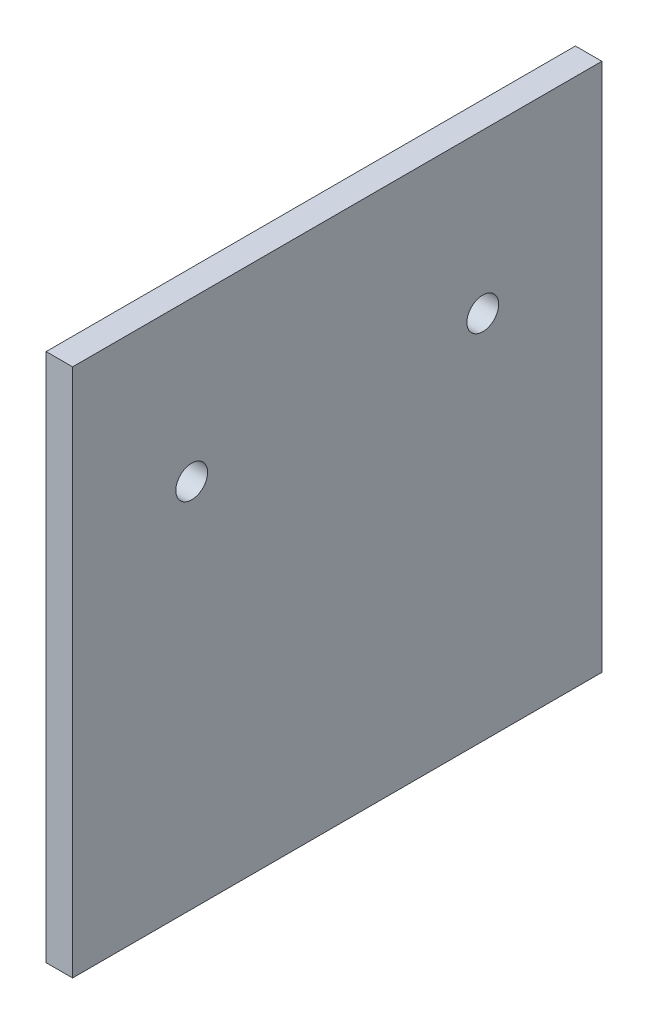
SolidWorks part; units mm, degrees
material "Plain Carbon Steel"
ref_plane "Front Plane" through (0, 0, 0) normal (0, 0, 1) x (1, 0, 0)
ref_plane "Top Plane" through (0, 0, 0) normal (0, 1, 0) x (1, 0, 0)
ref_plane "Right Plane" through (0, 0, 0) normal (1, 0, 0) x (0, 0, -1)
sketch "Sketch1" plane through (0, 0, 0) normal (1, 0, 0) x (0, 0, -1)
  line L1 (-100, -100) -> (100, -100)
  line L2 (-100, -100) -> (-100, 100)
  line L3 (-100, 100) -> (100, 100)
  line L4 (100, -100) -> (100, 100)
  line L5 (-100, -100) -> (100, 100) construction
  line L6 (-100, 100) -> (100, -100) construction
  point P0 (0, 0)
  dimension "D1" = 200
  dimension "D2" = 200
extrude "Boss-Extrude1" add sketch "Sketch1" along normal blind 10
sketch "Sketch2" plane through (10, 0, 0) normal (1, 0, 0) x (0, 0, -1)
  line L0 (100, 100) -> (-100, 100) construction
  circle A0 centre (-55, 40) radius 6
  circle A1 centre (55, 40) radius 6
  dimension "D1" = 12
  dimension "D2" = 12
  dimension "D3" = 110
  dimension "D4" = 55
  dimension "D5" = 60
extrude "Cut-Extrude1" cut sketch "Sketch2" against normal up to next
